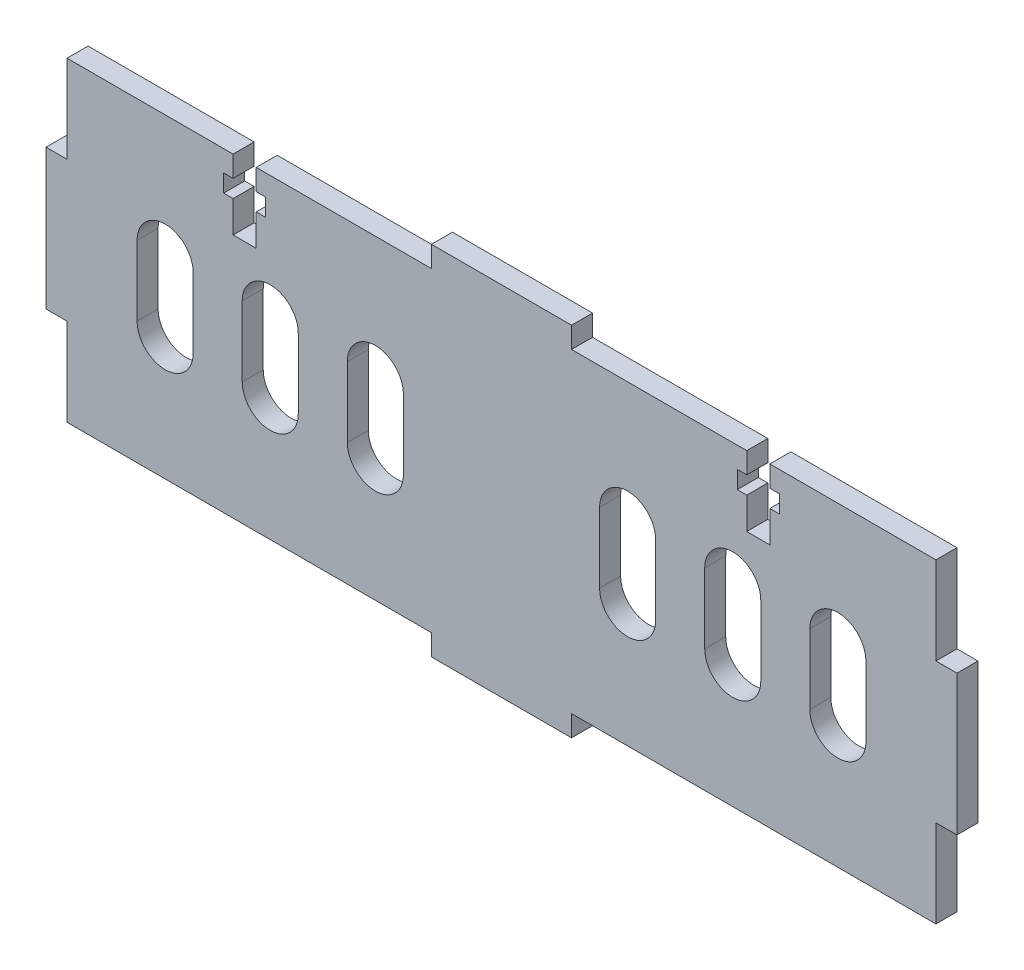
SolidWorks part; units mm, degrees
ref_plane "Front Plane" through (0, 0, 0) normal (0, 0, 1) x (1, 0, 0)
ref_plane "Top Plane" through (0, 0, 0) normal (0, 1, 0) x (1, 0, 0)
ref_plane "Right Plane" through (0, 0, 0) normal (1, 0, 0) x (0, 0, -1)
sketch "Sketch1" plane through (0, 0, 0) normal (0, 0, 1) x (1, 0, 0)
  line L1 (62, -22.5) -> (-62, -22.5)
  line L2 (62, -22.5) -> (62, 22.5)
  line L3 (62, 22.5) -> (-62, 22.5)
  line L4 (-62, -22.5) -> (-62, 22.5)
  line L5 (62, -22.5) -> (-62, 22.5) construction
  line L6 (62, 22.5) -> (-62, -22.5) construction
  line L9 (0, -55) -> (0, 55) construction
  line L16 (10, -25.5) -> (-10, -25.5)
  line L17 (10, -25.5) -> (10, -22.5)
  line L18 (10, -22.5) -> (-10, -22.5)
  line L19 (-10, -25.5) -> (-10, -22.5)
  line L20 (10, -25.5) -> (-10, -22.5) construction
  line L21 (10, -22.5) -> (-10, -25.5) construction
  line L22 (-65, -10) -> (-62, -10)
  line L23 (-65, -10) -> (-65, 10)
  line L24 (-65, 10) -> (-62, 10)
  line L25 (-62, -10) -> (-62, 10)
  line L26 (-65, -10) -> (-62, 10) construction
  line L27 (-65, 10) -> (-62, -10) construction
  line L28 (65, 10) -> (62, 10)
  line L29 (62, -10) -> (62, 10)
  line L30 (65, -10) -> (62, -10)
  line L31 (65, -10) -> (65, 10)
  line L32 (55, 0) -> (-55, 0) construction
  line L33 (10, 22.5) -> (-10, 22.5)
  line L34 (-10, 25.5) -> (-10, 22.5)
  line L35 (10, 25.5) -> (-10, 25.5)
  line L36 (10, 25.5) -> (10, 22.5)
  line L37 (33.65, 17) -> (39.65, 17)
  line L38 (-35, 12.5) -> (-38.3, 12.5)
  line L39 (-35, 12.5) -> (-35, 22.5)
  line L40 (-35, 22.5) -> (-38.3, 22.5)
  line L41 (-38.3, 12.5) -> (-38.3, 22.5)
  line L42 (-35, 12.5) -> (-38.3, 22.5) construction
  line L43 (-35, 22.5) -> (-38.3, 12.5) construction
  line L44 (-33.65, 19.5) -> (-39.65, 19.5)
  line L45 (-33.65, 19.5) -> (-33.65, 17)
  line L46 (-33.65, 17) -> (-39.65, 17)
  line L47 (-39.65, 19.5) -> (-39.65, 17)
  line L48 (-33.65, 19.5) -> (-39.65, 17) construction
  line L49 (-33.65, 17) -> (-39.65, 19.5) construction
  line L50 (39.65, 19.5) -> (39.65, 17)
  line L51 (33.65, 19.5) -> (39.65, 19.5)
  line L52 (33.65, 19.5) -> (33.65, 17)
  line L53 (35, 22.5) -> (38.3, 22.5)
  line L54 (38.3, 12.5) -> (38.3, 22.5)
  line L55 (35, 12.5) -> (38.3, 12.5)
  line L56 (35, 12.5) -> (35, 22.5)
  line L59 (-48, -5) -> (-48, 5) construction
  line L60 (-52, -5) -> (-52, 5)
  line L65 (-44, -5) -> (-44, 5)
  line L66 (-33, -5) -> (-33, 5) construction
  line L84 (-18, -5) -> (-18, 5) construction
  line L85 (-22, -5) -> (-22, 5)
  line L86 (-14, -5) -> (-14, 5)
  line L87 (-37, -5) -> (-37, 5)
  line L88 (-29, -5) -> (-29, 5)
  line L89 (18, -5) -> (18, 5) construction
  line L90 (22, -5) -> (22, 5)
  line L91 (14, -5) -> (14, 5)
  line L92 (33, -5) -> (33, 5) construction
  line L93 (37, -5) -> (37, 5)
  line L94 (29, -5) -> (29, 5)
  line L95 (48, -5) -> (48, 5) construction
  line L96 (52, -5) -> (52, 5)
  line L97 (44, -5) -> (44, 5)
  arc A0 (-52, -5) -> (-44, -5) centre (-48, -5) ccw
  arc A1 (-44, 5) -> (-52, 5) centre (-48, 5) ccw
  arc A4 (-22, -5) -> (-14, -5) centre (-18, -5) ccw
  arc A5 (-14, 5) -> (-22, 5) centre (-18, 5) ccw
  arc A6 (-37, -5) -> (-29, -5) centre (-33, -5) ccw
  arc A7 (-29, 5) -> (-37, 5) centre (-33, 5) ccw
  arc A8 (22, -5) -> (14, -5) centre (18, -5) cw
  arc A9 (14, 5) -> (22, 5) centre (18, 5) cw
  arc A10 (37, -5) -> (29, -5) centre (33, -5) cw
  arc A11 (29, 5) -> (37, 5) centre (33, 5) cw
  arc A12 (52, -5) -> (44, -5) centre (48, -5) cw
  arc A13 (44, 5) -> (52, 5) centre (48, 5) cw
  point P0 (0, 0)
  point P8 (-48, 0)
  point P15 (-33, 0)
  point P17 (-36.65, 17.5)
  point P18 (-63.5, 0)
  point P22 (-18, 0)
  point P30 (0, 0)
  point P31 (0, -24)
  point P55 (-36.65, 18.25)
  point P60 (-48, 2.0368)
  point P69 (0, 0)
  point P72 (18, 0)
  point P79 (33, 0)
  point P86 (48, 0)
  dimension "D3" = 4
  dimension "D4" = 10
  dimension "D1" = 124
  dimension "D2" = 45
  dimension "D5" = 10
  dimension "D6" = 7
  dimension "D7" = 7
  dimension "D14" = 20
  dimension "D15" = 3
  dimension "D16" = 20
  dimension "D17" = 3
  dimension "D18" = 3.3
  dimension "D19" = 10
  dimension "D20" = 6
  dimension "D21" = 2.5
  dimension "D22" = 3
  dimension "D23" = 25
extrude "Boss-Extrude1" add sketch "Sketch1" along normal blind 3
